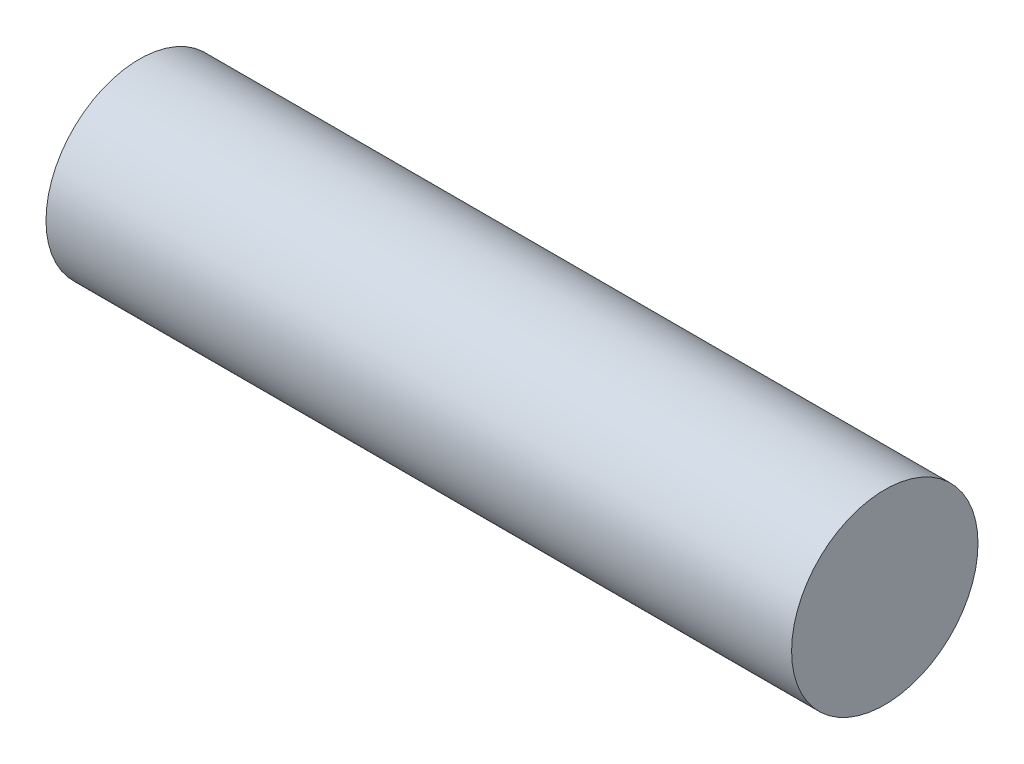
SolidWorks part; units mm, degrees
material "CMR DEFAULT - CHANGE MATERIAL"
ref_plane "XY PLANE - TOP" through (0, 0, 0) normal (0, 0, 1) x (1, 0, 0)
ref_plane "XZ PLANE - SIDE" through (0, 0, 0) normal (0, 1, 0) x (1, 0, 0)
ref_plane "YZ PLANE - FRONT" through (0, 0, 0) normal (1, 0, 0) x (0, 0, -1)
sketch "Sketch1" plane through (0, 0, 0) normal (1, 0, 0) x (0, 0, -1)
  circle A0 centre (0, 0) radius 3.175
  dimension "D1" = 6.35
extrude "Boss-Extrude1" add sketch "Sketch1" along normal blind 25.4
